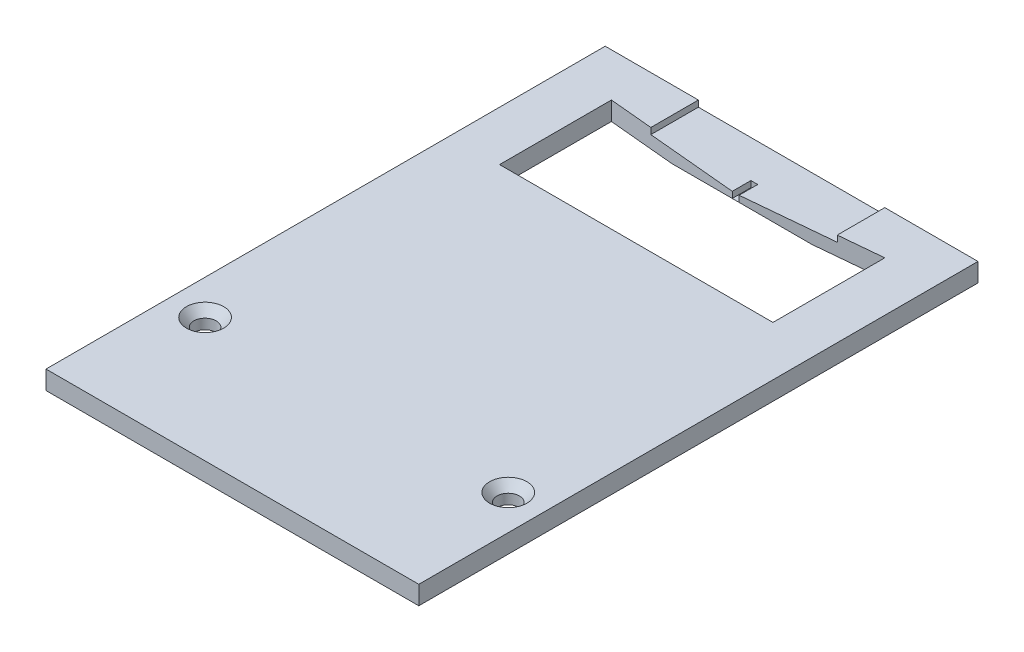
SolidWorks part; units mm, degrees
ref_plane "Front Plane" through (0, 0, 0) normal (0, 0, 1) x (1, 0, 0)
ref_plane "Top Plane" through (0, 0, 0) normal (0, 1, 0) x (1, 0, 0)
ref_plane "Right Plane" through (0, 0, 0) normal (1, 0, 0) x (0, 0, -1)
sketch "Sketch1" plane through (0, 0, 0) normal (0, 1, 0) x (1, 0, 0)
  line L0 (-22, 45) -> (22, 45)
  line L1 (-22, 61) -> (-22, 45)
  line L2 (-30, 20) -> (-30, -20)
  line L3 (-30, -20) -> (30, -20)
  line L4 (30, 20) -> (30, -20)
  line L5 (-22, 70) -> (22, 70)
  line L6 (-30, 20) -> (-30, 70)
  line L7 (-30, 70) -> (-22, 70)
  line L8 (22, 61) -> (22, 45)
  line L9 (30, 20) -> (30, 70)
  line L10 (30, 70) -> (22, 70)
  line L13 (-22, 61) -> (22, 61)
extrude "Boss-Extrude1" add sketch "Sketch1" along normal blind 3
sketch "Sketch3" plane through (0, 3, 0) normal (0, 1, 0) x (1, 0, 0)
  line L0 (22, 61) -> (-22, 61) construction
  line L1 (-15, 61) -> (15, 61)
  line L2 (-15, 61) -> (-15, 70)
  line L3 (-15, 70) -> (15, 70)
  line L4 (15, 61) -> (15, 70)
  line L5 (30, 70) -> (-30, 70) construction
  line L6 (0, 70) -> (0, 61) construction
  line L7 (-30, 70) -> (-30, -20) construction
  line L8 (30, -20) -> (30, 70) construction
  dimension "D1" = 15
extrude "Cut-Extrude2" cut sketch "Sketch3" against normal blind 1
sketch "Sketch4" plane through (0, 2, 0) normal (0, 1, 0) x (1, 0, 0)
  line L0 (-15, 61) -> (15, 61) construction
  line L1 (-0.55, 64) -> (0.55, 64)
  line L2 (-0.55, 64) -> (-0.55, 61)
  line L3 (-0.55, 61) -> (0.55, 61)
  line L4 (0.55, 64) -> (0.55, 61)
extrude "Cut-Extrude3" cut sketch "Sketch4" against normal blind 1
sketch "Sketch5" plane through (0, 3, 0) normal (0, 1, 0) x (1, 0, 0)
  circle A0 centre (24.4, 0) radius 3
  circle A1 centre (-24.4, 0) radius 3
extrude "Cut-Extrude4" cut sketch "Sketch5" against normal through all draft 41
sketch "Sketch7" plane through (0, 3, 0) normal (0, 1, 0) x (1, 0, 0)
  circle A0 centre (-24.4, 0) radius 1.8
  circle A1 centre (24.4, 0) radius 1.8
extrude "Cut-Extrude5" cut sketch "Sketch7" against normal through all
sketch "Sketch8" plane through (0, 3, 0) normal (0, 1, 0) x (1, 0, 0)
  line L0 (-22, 61) -> (-0.55, 61)
  line L1 (-0.55, 61) -> (-22, 63)
  line L2 (-22, 63) -> (-22, 61)
  line L3 (22, 61) -> (0.55, 61)
  line L4 (0.55, 61) -> (22, 63)
  line L5 (22, 63) -> (22, 61)
extrude "Cut-Extrude7" cut sketch "Sketch8" against normal through all
sketch "Sketch9" plane through (0, 0, 0) normal (0, -1, 0) x (1, 0, 0)
  line L0 (22, -45) -> (22, -63) construction
  line L1 (22, -62) -> (-22, -62)
  line L2 (22, -62) -> (22, -60)
  line L3 (22, -60) -> (-22, -60)
  line L4 (-22, -62) -> (-22, -60)
  line L5 (-22, -63) -> (-22, -45) construction
extrude "Cut-Extrude8" cut sketch "Sketch9" against normal blind 1 draft 45
